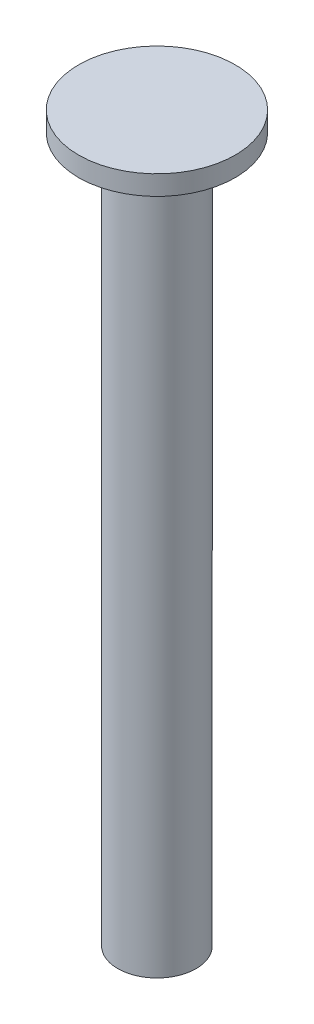
SolidWorks part; units mm, degrees
material "合金钢"
ref_plane "前视基准面" through (0, 0, 0) normal (0, 0, 1) x (1, 0, 0)
ref_plane "上视基准面" through (0, 0, 0) normal (0, 1, 0) x (1, 0, 0)
ref_plane "右视基准面" through (0, 0, 0) normal (1, 0, 0) x (0, 0, -1)
sketch "草图1" plane through (0, 0, 0) normal (0, 1, 0) x (1, 0, 0)
  circle A0 centre (0, 0) radius 2
  dimension "D1" = 4
extrude "凸台-拉伸1" add sketch "草图1" along normal blind 0.5
sketch "草图2" plane through (0, 0, 0) normal (0, -1, 0) x (1, 0, 0)
  circle A0 centre (0, 0) radius 1
  dimension "D1" = 2
extrude "凸台-拉伸2" add sketch "草图2" along normal blind 18
